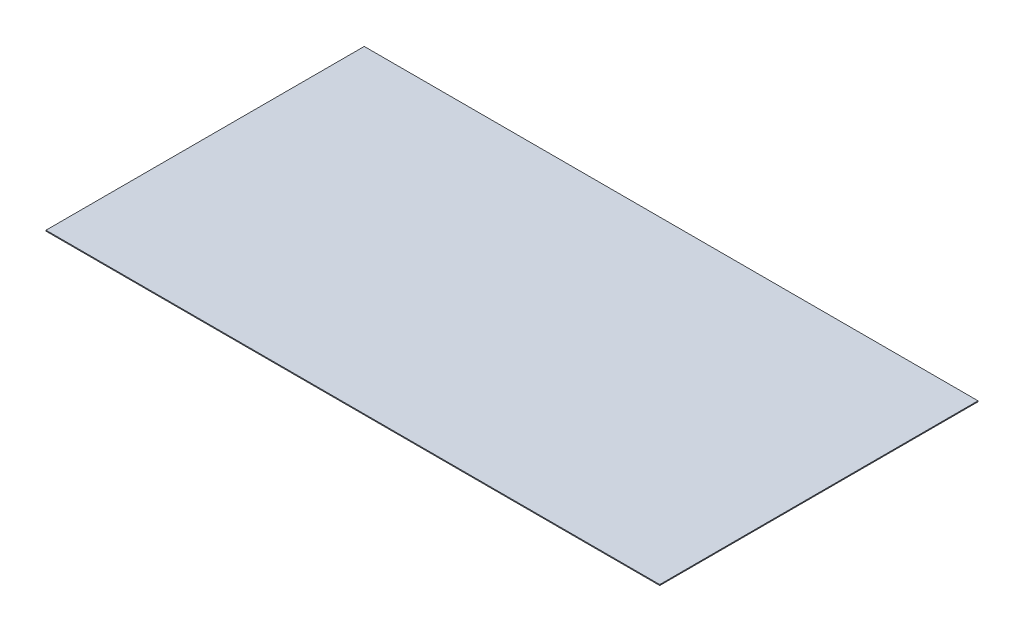
SolidWorks part; units mm, degrees
ref_plane "Спереди" through (0, 0, 0) normal (0, 0, 1) x (1, 0, 0)
ref_plane "Сверху" through (0, 0, 0) normal (0, 1, 0) x (1, 0, 0)
ref_plane "Справа" through (0, 0, 0) normal (1, 0, 0) x (0, 0, -1)
sketch "MASTER_FOOTPRINT" plane through (0, 0, 0) normal (0, 1, 0) x (1, 0, 0)
  line L1 (0, 0) -> (1350, 0)
  line L2 (0, 0) -> (0, 700)
  line L3 (0, 700) -> (1350, 700)
  line L4 (1350, 0) -> (1350, 700)
extrude "BATH_BASE_PLATE" add sketch "MASTER_FOOTPRINT" along normal blind 2
equation "\"AI_Q_Peak\"= 0.006"
equation "\"AI_B_Bath\"= 700"
equation "\"AI_L_Settle\"= 900"
equation "\"AI_L_Inlet\"= 250"
equation "\"AI_L_Outlet\"= 200"
equation "\"AI_L_Bath\"= 1350"
equation "\"AI_H_Water\"= 550"
equation "\"AI_H_Freeboard\"= 200"
equation "\"AI_H_Bath\"= 750"
equation "\"AI_Shell_Thickness\"= 2"
equation "\"AI_Inlet_DN\"= 100"
equation "\"AI_Weir_Width\"= 600"
equation "\"AI_Inlet_Baffle_Offset\"= 125"
equation "\"AI_Distributor_Open_Area\"= 0.28"
equation "\"AI_Distributor_Hole_Dia\"= 22"
equation "\"AI_Distributor_Blind_Zone\"= 110"
equation "\"AI_Outlet_Baffle_Depth\"= 250"
equation "\"AI_Screw_Diameter\"= 100"
equation "\"AI_Screw_Pitch\"= 100"
equation "\"AI_Screw_Angle\"= 30"
equation "\"AI_Screw_Rpm\"= 15"
equation "\"AI_Screw_Clearance\"= 5"
equation "\"AI_Liner_Thickness\"= 5"
equation "\"AI_Discharge_Height\"= 650"
equation "\"AI_Frame_Height\"= 500"
